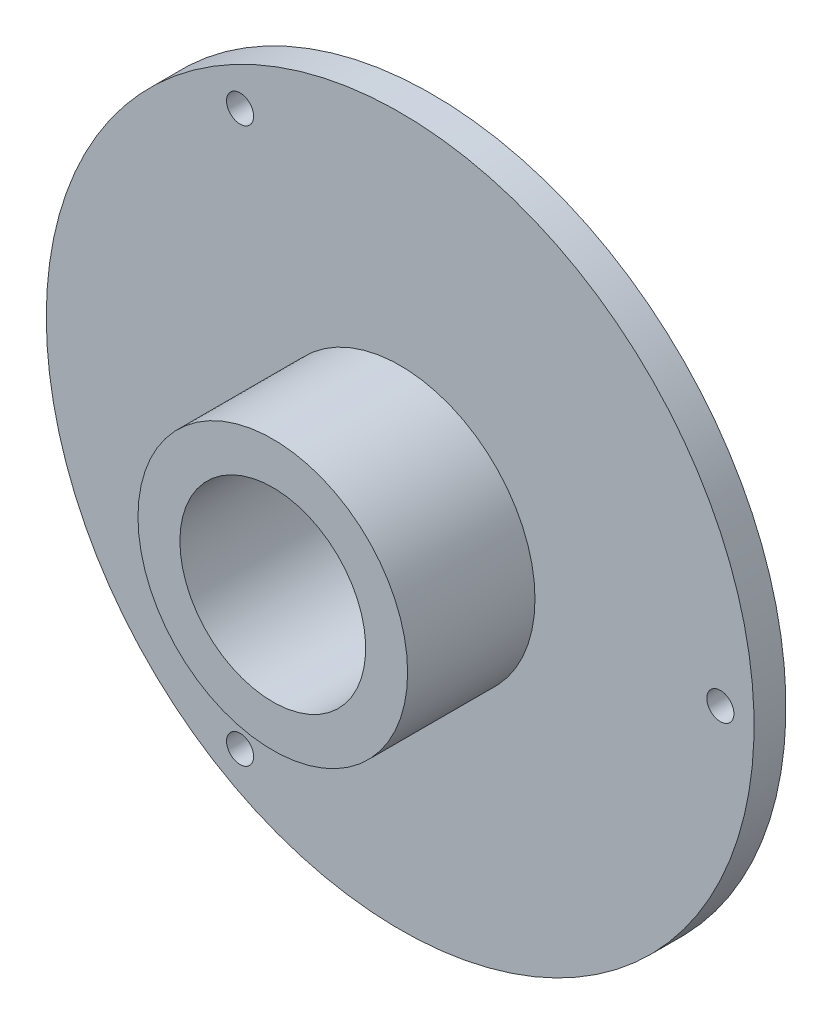
SolidWorks part; units mm, degrees
material "6061-T6 (SS)"
ref_plane "Front Plane" through (0, 0, 0) normal (0, 0, 1) x (1, 0, 0)
ref_plane "Top Plane" through (0, 0, 0) normal (0, 1, 0) x (1, 0, 0)
ref_plane "Right Plane" through (0, 0, 0) normal (1, 0, 0) x (0, 0, -1)
curve "Volute Curve"
  spline degree 3 poles (35.9487, 0, 0) (35.9516, 0.0754, 0) (35.9573, 0.2262, 0) (35.9642, 0.4524, 0) (35.9698, 0.6788, 0) (35.9739, 0.9052, 0) (35.9766, 1.1318, 0) (35.9779, 1.3583, 0) (35.9778, 1.585, 0) (35.9763, 1.8117, 0) (35.9733, 2.0385, 0) (35.969, 2.2653, 0) (35.9632, 2.4921, 0) (35.956, 2.7189, 0) (35.9473, 2.9457, 0) (35.9373, 3.1726, 0) (35.9258, 3.3994, 0) (35.9129, 3.6262, 0) (35.8986, 3.853, 0) (35.8828, 4.0798, 0) (35.8656, 4.3065, 0) (35.847, 4.5331, 0) (35.827, 4.7597, 0) (35.8055, 4.9862, 0) (35.7826, 5.2127, 0) (35.7583, 5.439, 0) (35.7326, 5.6653, 0) (35.7054, 5.8914, 0) (35.6768, 6.1174, 0) (35.6468, 6.3433, 0) (35.6153, 6.5691, 0) (35.5825, 6.7947, 0) (35.5482, 7.0201, 0) (35.5124, 7.2455, 0) (35.4753, 7.4706, 0) (35.4367, 7.6955, 0) (35.3967, 7.9203, 0) (35.3553, 8.1449, 0) (35.3125, 8.3692, 0) (35.2683, 8.5934, 0) (35.2226, 8.8173, 0) (35.1755, 9.041, 0) (35.127, 9.2644, 0) (35.0771, 9.4876, 0) (35.0257, 9.7105, 0) (34.973, 9.9332, 0) (34.9188, 10.1556, 0) (34.8633, 10.3777, 0) (34.8063, 10.5995, 0) (34.7479, 10.821, 0) (34.6881, 11.0422, 0) (34.6269, 11.263, 0) (34.5643, 11.4836, 0) (34.5004, 11.7037, 0) (34.435, 11.9236, 0) (34.3682, 12.1431, 0) (34.3, 12.3622, 0) (34.2304, 12.5809, 0) (34.1594, 12.7993, 0) (34.0871, 13.0172, 0) (34.0133, 13.2348, 0) (33.9382, 13.4519, 0) (33.8617, 13.6686, 0) (33.7838, 13.8849, 0) (33.7045, 14.1008, 0) (33.6238, 14.3162, 0) (33.5418, 14.5311, 0) (33.4584, 14.7456, 0) (33.3737, 14.9596, 0) (33.2875, 15.1732, 0) (33.2, 15.3862, 0) (33.1112, 15.5988, 0) (33.021, 15.8108, 0) (32.9294, 16.0223, 0) (32.8365, 16.2333, 0) (32.7422, 16.4438, 0) (32.6466, 16.6537, 0) (32.5497, 16.8631, 0) (32.4514, 17.0719, 0) (32.3517, 17.2801, 0) (32.2508, 17.4878, 0) (32.1485, 17.6949, 0) (32.0448, 17.9013, 0) (31.9399, 18.1072, 0) (31.8336, 18.3125, 0) (31.7261, 18.5171, 0) (31.6172, 18.7212, 0) (31.507, 18.9246, 0) (31.3955, 19.1273, 0) (31.2827, 19.3294, 0) (31.1685, 19.5308, 0) (31.0531, 19.7316, 0) (30.9365, 19.9317, 0) (30.8185, 20.1311, 0) (30.6992, 20.3298, 0) (30.5787, 20.5278, 0) (30.4569, 20.7251, 0) (30.3338, 20.9217, 0) (30.2094, 21.1175, 0) (30.0838, 21.3126, 0) (29.957, 21.507, 0) (29.8288, 21.7006, 0) (29.6995, 21.8935, 0) (29.5689, 22.0856, 0) (29.437, 22.2769, 0) (29.3039, 22.4674, 0) (29.1696, 22.6571, 0) (29.0341, 22.8461, 0) (28.8973, 23.0342, 0) (28.7593, 23.2215, 0) (28.6201, 23.408, 0) (28.4797, 23.5937, 0) (28.3381, 23.7785, 0) (28.1953, 23.9625, 0) (28.0514, 24.1456, 0) (27.9062, 24.3279, 0) (27.7598, 24.5093, 0) (27.6123, 24.6898, 0) (27.4636, 24.8694, 0) (27.3137, 25.0482, 0) (27.1627, 25.226, 0) (27.0105, 25.403, 0) (26.8572, 25.579, 0) (26.7027, 25.7541, 0) (26.5471, 25.9282, 0) (26.3903, 26.1015, 0) (26.2325, 26.2738, 0) (26.0735, 26.4451, 0) (25.9134, 26.6155, 0) (25.7521, 26.7849, 0) (25.5898, 26.9533, 0) (25.4264, 27.1208, 0) (25.2619, 27.2872, 0) (25.0963, 27.4527, 0) (24.9296, 27.6172, 0) (24.7618, 27.7806, 0) (24.593, 27.9431, 0) (24.4231, 28.1045, 0) (24.2521, 28.2649, 0) (24.0802, 28.4242, 0) (23.9071, 28.5825, 0) (23.733, 28.7398, 0) (23.5579, 28.896, 0) (23.3818, 29.0511, 0) (23.2046, 29.2052, 0) (23.0265, 29.3582, 0) (22.8473, 29.5101, 0) (22.6671, 29.6609, 0) (22.486, 29.8106, 0) (22.3038, 29.9592, 0) (22.1207, 30.1067, 0) (21.9366, 30.2531, 0) (21.7515, 30.3984, 0) (21.5655, 30.5425, 0) (21.3785, 30.6855, 0) (21.1906, 30.8274, 0) (21.0018, 30.9681, 0) (20.812, 31.1076, 0) (20.6213, 31.246, 0) (20.4297, 31.3833, 0) (20.2371, 31.5193, 0) (20.0437, 31.6542, 0) (19.8494, 31.7879, 0) (19.6541, 31.9204, 0) (19.458, 32.0517, 0) (19.2611, 32.1818, 0) (19.0632, 32.3106, 0) (18.8645, 32.4383, 0) (18.665, 32.5648, 0) (18.4646, 32.69, 0) (18.2634, 32.814, 0) (18.0613, 32.9368, 0) (17.8584, 33.0583, 0) (17.6547, 33.1786, 0) (17.4502, 33.2976, 0) (17.2449, 33.4154, 0) (17.0389, 33.5319, 0) (16.832, 33.6471, 0) (16.6244, 33.761, 0) (16.4159, 33.8737, 0) (16.2068, 33.9851, 0) (15.9969, 34.0952, 0) (15.7862, 34.204, 0) (15.5748, 34.3115, 0) (15.3627, 34.4177, 0) (15.1498, 34.5226, 0) (14.9363, 34.6262, 0) (14.722, 34.7285, 0) (14.5071, 34.8294, 0) (14.2914, 34.929, 0) (14.0751, 35.0273, 0) (13.8581, 35.1242, 0) (13.6405, 35.2198, 0) (13.4222, 35.3141, 0) (13.2032, 35.407, 0) (12.9836, 35.4985, 0) (12.7634, 35.5887, 0) (12.5426, 35.6775, 0) (12.3212, 35.765, 0) (12.0991, 35.8511, 0) (11.8765, 35.9358, 0) (11.6532, 36.0191, 0) (11.4294, 36.101, 0) (11.205, 36.1816, 0) (10.9801, 36.2607, 0) (10.7546, 36.3385, 0) (10.5286, 36.4148, 0) (10.302, 36.4898, 0) (10.0749, 36.5633, 0) (9.8473, 36.6355, 0) (9.6192, 36.7062, 0) (9.3906, 36.7755, 0) (9.1615, 36.8434, 0) (8.9319, 36.9098, 0) (8.7018, 36.9748, 0) (8.4713, 37.0384, 0) (8.2403, 37.1006, 0) (8.0089, 37.1613, 0) (7.777, 37.2206, 0) (7.5447, 37.2784, 0) (7.312, 37.3348, 0) (7.0789, 37.3897, 0) (6.8453, 37.4432, 0) (6.6114, 37.4952, 0) (6.3771, 37.5458, 0) (6.1424, 37.5949, 0) (5.9074, 37.6425, 0) (5.672, 37.6887, 0) (5.4362, 37.7334, 0) (5.2002, 37.7766, 0) (4.9637, 37.8183, 0) (4.727, 37.8586, 0) (4.49, 37.8974, 0) (4.2526, 37.9347, 0) (4.015, 37.9705, 0) (3.7771, 38.0048, 0) (3.5389, 38.0377, 0) (3.3004, 38.069, 0) (3.0617, 38.0989, 0) (2.8228, 38.1273, 0) (2.5836, 38.1541, 0) (2.3442, 38.1795, 0) (2.1046, 38.2034, 0) (1.8647, 38.2257, 0) (1.6247, 38.2466, 0) (1.3845, 38.2659, 0) (1.1441, 38.2838, 0) (0.9035, 38.3001, 0) (0.6628, 38.315, 0) (0.4219, 38.3283, 0) (0.1808, 38.3401, 0) (-0.0603, 38.3504, 0) (-0.3016, 38.3591, 0) (-0.543, 38.3664, 0) (-0.7845, 38.3721, 0) (-1.0261, 38.3764, 0) (-1.2677, 38.3791, 0) (-1.5095, 38.3802, 0) (-1.7513, 38.3799, 0) (-1.9932, 38.378, 0) (-2.2351, 38.3746, 0) (-2.477, 38.3697, 0) (-2.719, 38.3633, 0) (-2.961, 38.3554, 0) (-3.203, 38.3459, 0) (-3.445, 38.3349, 0) (-3.687, 38.3223, 0) (-3.929, 38.3083, 0) (-4.1709, 38.2927, 0) (-4.4128, 38.2756, 0) (-4.6546, 38.2569, 0) (-4.8964, 38.2368, 0) (-5.1381, 38.2151, 0) (-5.3798, 38.1919, 0) (-5.6213, 38.1671, 0) (-5.8628, 38.1408, 0) (-6.1041, 38.113, 0) (-6.3453, 38.0837, 0) (-6.5864, 38.0529, 0) (-6.8274, 38.0205, 0) (-7.0682, 37.9866, 0) (-7.3089, 37.9512, 0) (-7.5494, 37.9142, 0) (-7.7897, 37.8758, 0) (-8.0298, 37.8358, 0) (-8.2698, 37.7943, 0) (-8.5095, 37.7512, 0) (-8.749, 37.7067, 0) (-8.9883, 37.6606, 0) (-9.2274, 37.613, 0) (-9.4662, 37.5639, 0) (-9.7048, 37.5133, 0) (-9.9431, 37.4612, 0) (-10.1811, 37.4076, 0) (-10.4189, 37.3524, 0) (-10.6563, 37.2957, 0) (-10.8935, 37.2376, 0) (-11.1303, 37.1779, 0) (-11.3669, 37.1167, 0) (-11.6031, 37.054, 0) (-11.8389, 36.9898, 0) (-12.0745, 36.9241, 0) (-12.3096, 36.857, 0) (-12.5444, 36.7883, 0) (-12.7788, 36.7181, 0) (-13.0129, 36.6464, 0) (-13.2465, 36.5733, 0) (-13.4797, 36.4986, 0) (-13.7126, 36.4225, 0) (-13.9449, 36.3449, 0) (-14.1769, 36.2658, 0) (-14.4084, 36.1852, 0) (-14.6395, 36.1032, 0) (-14.8701, 36.0196, 0) (-15.1002, 35.9346, 0) (-15.3299, 35.8482, 0) (-15.559, 35.7602, 0) (-15.7877, 35.6708, 0) (-16.0159, 35.58, 0) (-16.2435, 35.4877, 0) (-16.4706, 35.3939, 0) (-16.6972, 35.2987, 0) (-16.9232, 35.202, 0) (-17.1487, 35.1039, 0) (-17.3736, 35.0043, 0) (-17.5979, 34.9033, 0) (-17.8217, 34.8009, 0) (-18.0448, 34.697, 0) (-18.2674, 34.5917, 0) (-18.4893, 34.485, 0) (-18.7107, 34.3769, 0) (-18.9314, 34.2673, 0) (-19.1514, 34.1563, 0) (-19.3708, 34.044, 0) (-19.5896, 33.9302, 0) (-19.8077, 33.815, 0) (-20.0251, 33.6984, 0) (-20.2419, 33.5804, 0) (-20.4579, 33.461, 0) (-20.6733, 33.3402, 0) (-20.8879, 33.218, 0) (-21.1018, 33.0945, 0) (-21.315, 32.9696, 0) (-21.5275, 32.8433, 0) (-21.7392, 32.7156, 0) (-21.9501, 32.5866, 0) (-22.1603, 32.4562, 0) (-22.3698, 32.3245, 0) (-22.5784, 32.1914, 0) (-22.7863, 32.057, 0) (-22.9933, 31.9212, 0) (-23.1996, 31.7841, 0) (-23.405, 31.6457, 0) (-23.6097, 31.5059, 0) (-23.8134, 31.3648, 0) (-24.0164, 31.2224, 0) (-24.2185, 31.0787, 0) (-24.4197, 30.9337, 0) (-24.6201, 30.7874, 0) (-24.8196, 30.6398, 0) (-25.0182, 30.4909, 0) (-25.216, 30.3407, 0) (-25.4128, 30.1892, 0) (-25.6087, 30.0365, 0) (-25.8037, 29.8825, 0) (-25.9978, 29.7272, 0) (-26.191, 29.5707, 0) (-26.3832, 29.4129, 0) (-26.5745, 29.2539, 0) (-26.7648, 29.0936, 0) (-26.9541, 28.9321, 0) (-27.1425, 28.7693, 0) (-27.3299, 28.6054, 0) (-27.5163, 28.4402, 0) (-27.7017, 28.2738, 0) (-27.8861, 28.1062, 0) (-28.0695, 27.9374, 0) (-28.2519, 27.7674, 0) (-28.4332, 27.5962, 0) (-28.6135, 27.4238, 0) (-28.7928, 27.2503, 0) (-28.971, 27.0756, 0) (-29.1482, 26.8997, 0) (-29.3243, 26.7227, 0) (-29.4993, 26.5445, 0) (-29.6733, 26.3652, 0) (-29.8461, 26.1847, 0) (-30.0179, 26.0031, 0) (-30.1885, 25.8204, 0) (-30.3581, 25.6366, 0) (-30.5265, 25.4516, 0) (-30.6938, 25.2656, 0) (-30.86, 25.0784, 0) (-31.025, 24.8902, 0) (-31.1889, 24.7009, 0) (-31.3516, 24.5105, 0) (-31.5132, 24.319, 0) (-31.6736, 24.1265, 0) (-31.8329, 23.9329, 0) (-31.9909, 23.7382, 0) (-32.1478, 23.5426, 0) (-32.3034, 23.3459, 0) (-32.4579, 23.1481, 0) (-32.6112, 22.9494, 0) (-32.7632, 22.7496, 0) (-32.914, 22.5489, 0) (-33.0636, 22.3471, 0) (-33.212, 22.1443, 0) (-33.3591, 21.9406, 0) (-33.505, 21.7359, 0) (-33.6496, 21.5302, 0) (-33.7929, 21.3236, 0) (-33.935, 21.116, 0) (-34.0758, 20.9075, 0) (-34.2154, 20.698, 0) (-34.3536, 20.4876, 0) (-34.4906, 20.2763, 0) (-34.6262, 20.0641, 0) (-34.7606, 19.851, 0) (-34.8936, 19.637, 0) (-35.0253, 19.4221, 0) (-35.1557, 19.2063, 0) (-35.2848, 18.9896, 0) (-35.4126, 18.7721, 0) (-35.539, 18.5537, 0) (-35.664, 18.3345, 0) (-35.7877, 18.1144, 0) (-35.9101, 17.8935, 0) (-36.0311, 17.6718, 0) (-36.1507, 17.4493, 0) (-36.2689, 17.2259, 0) (-36.3858, 17.0018, 0) (-36.5013, 16.7769, 0) (-36.6154, 16.5512, 0) (-36.7281, 16.3247, 0) (-36.8394, 16.0975, 0) (-36.9493, 15.8695, 0) (-37.0578, 15.6408, 0) (-37.1649, 15.4113, 0) (-37.2705, 15.1811, 0) (-37.3748, 14.9502, 0) (-37.4776, 14.7186, 0) (-37.5789, 14.4862, 0) (-37.6789, 14.2532, 0) (-37.7773, 14.0195, 0) (-37.8744, 13.7851, 0) (-37.97, 13.5501, 0) (-38.0641, 13.3144, 0) (-38.1567, 13.078, 0) (-38.2479, 12.8411, 0) (-38.3377, 12.6034, 0) (-38.4259, 12.3652, 0) (-38.5127, 12.1264, 0) (-38.598, 11.8869, 0) (-38.6818, 11.6469, 0) (-38.7641, 11.4062, 0) (-38.8449, 11.165, 0) (-38.9242, 10.9233, 0) (-39.002, 10.6809, 0) (-39.0783, 10.4381, 0) (-39.1531, 10.1947, 0) (-39.2264, 9.9507, 0) (-39.2982, 9.7063, 0) (-39.3684, 9.4613, 0) (-39.4371, 9.2159, 0) (-39.5043, 8.9699, 0) (-39.57, 8.7235, 0) (-39.6341, 8.4766, 0) (-39.6966, 8.2292, 0) (-39.7577, 7.9814, 0) (-39.8172, 7.7332, 0) (-39.8751, 7.4845, 0) (-39.9315, 7.2354, 0) (-39.9863, 6.9858, 0) (-40.0396, 6.7359, 0) (-40.0913, 6.4856, 0) (-40.1414, 6.2349, 0) (-40.19, 5.9838, 0) (-40.237, 5.7324, 0) (-40.2825, 5.4806, 0) (-40.3263, 5.2284, 0) (-40.3686, 4.976, 0) (-40.4093, 4.7232, 0) (-40.4484, 4.47, 0) (-40.486, 4.2166, 0) (-40.5219, 3.9629, 0) (-40.5563, 3.7089, 0) (-40.5891, 3.4546, 0) (-40.6203, 3.2001, 0) (-40.6498, 2.9453, 0) (-40.6778, 2.6902, 0) (-40.7042, 2.435, 0) (-40.729, 2.1795, 0) (-40.7522, 1.9237, 0) (-40.7738, 1.6678, 0) (-40.7937, 1.4117, 0) (-40.8121, 1.1554, 0) (-40.8289, 0.8989, 0) (-40.844, 0.6423, 0) (-40.8575, 0.3855, 0) (-40.8695, 0.1285, 0) (-40.8798, -0.1286, 0) (-40.8884, -0.3858, 0) (-40.8955, -0.6431, 0) (-40.901, -0.9005, 0) (-40.9048, -1.158, 0) (-40.907, -1.4156, 0) (-40.9076, -1.6733, 0) (-40.9066, -1.931, 0) (-40.9039, -2.1888, 0) (-40.8996, -2.4467, 0) (-40.8937, -2.7045, 0) (-40.8862, -2.9624, 0) (-40.8771, -3.2203, 0) (-40.8663, -3.4782, 0) (-40.8539, -3.7361, 0) (-40.8399, -3.994, 0) (-40.8242, -4.2519, 0) (-40.8069, -4.5097, 0) (-40.788, -4.7674, 0) (-40.7675, -5.0251, 0) (-40.7453, -5.2828, 0) (-40.7215, -5.5403, 0) (-40.6961, -5.7978, 0) (-40.669, -6.0552, 0) (-40.6404, -6.3124, 0) (-40.6101, -6.5695, 0) (-40.5781, -6.8265, 0) (-40.5446, -7.0834, 0) (-40.5094, -7.3401, 0) (-40.4726, -7.5967, 0) (-40.4342, -7.853, 0) (-40.3941, -8.1092, 0) (-40.3525, -8.3652, 0) (-40.3092, -8.621, 0) (-40.2643, -8.8766, 0) (-40.2177, -9.1319, 0) (-40.1696, -9.3871, 0) (-40.1198, -9.6419, 0) (-40.0684, -9.8966, 0) (-40.0154, -10.1509, 0) (-39.9608, -10.405, 0) (-39.9046, -10.6588, 0) (-39.8468, -10.9123, 0) (-39.7873, -11.1655, 0) (-39.7263, -11.4184, 0) (-39.6636, -11.6709, 0) (-39.5994, -11.9232, 0) (-39.5335, -12.175, 0) (-39.466, -12.4265, 0) (-39.397, -12.6777, 0) (-39.3263, -12.9285, 0) (-39.254, -13.1789, 0) (-39.1802, -13.4288, 0) (-39.1048, -13.6784, 0) (-39.0277, -13.9276, 0) (-38.9491, -14.1763, 0) (-38.8689, -14.4246, 0) (-38.7871, -14.6725, 0) (-38.7038, -14.9199, 0) (-38.6188, -15.1668, 0) (-38.5323, -15.4132, 0) (-38.4442, -15.6592, 0) (-38.3546, -15.9047, 0) (-38.2634, -16.1496, 0) (-38.1706, -16.3941, 0) (-38.0762, -16.638, 0) (-37.9803, -16.8813, 0) (-37.8829, -17.1242, 0) (-37.7839, -17.3664, 0) (-37.6833, -17.6081, 0) (-37.5812, -17.8492, 0) (-37.4776, -18.0898, 0) (-37.3724, -18.3297, 0) (-37.2657, -18.569, 0) (-37.1574, -18.8077, 0) (-37.0477, -19.0458, 0) (-36.9364, -19.2833, 0) (-36.8236, -19.5201, 0) (-36.7092, -19.7562, 0) (-36.5934, -19.9917, 0) (-36.476, -20.2265, 0) (-36.3572, -20.4606, 0) (-36.2368, -20.694, 0) (-36.1149, -20.9268, 0) (-35.9916, -21.1588, 0) (-35.8667, -21.3901, 0) (-35.7404, -21.6206, 0) (-35.6126, -21.8504, 0) (-35.4833, -22.0795, 0) (-35.3526, -22.3078, 0) (-35.2203, -22.5353, 0) (-35.0867, -22.762, 0) (-34.9515, -22.988, 0) (-34.8149, -23.2131, 0) (-34.6769, -23.4375, 0) (-34.5374, -23.661, 0) (-34.3964, -23.8837, 0) (-34.2541, -24.1056, 0) (-34.1103, -24.3266, 0) (-33.9651, -24.5468, 0) (-33.8184, -24.7661, 0) (-33.6704, -24.9845, 0) (-33.5209, -25.202, 0) (-33.3701, -25.4187, 0) (-33.2178, -25.6345, 0) (-33.0641, -25.8493, 0) (-32.9091, -26.0632, 0) (-32.7527, -26.2762, 0) (-32.5949, -26.4883, 0) (-32.4357, -26.6994, 0) (-32.2751, -26.9096, 0) (-32.1132, -27.1188, 0) (-31.95, -27.327, 0) (-31.7854, -27.5343, 0) (-31.6194, -27.7405, 0) (-31.4522, -27.9458, 0) (-31.2835, -28.15, 0) (-31.1136, -28.3533, 0) (-30.9424, -28.5555, 0) (-30.7698, -28.7567, 0) (-30.5959, -28.9568, 0) (-30.4207, -29.1559, 0) (-30.2443, -29.354, 0) (-30.0665, -29.5509, 0) (-29.8875, -29.7468, 0) (-29.7072, -29.9417, 0) (-29.5256, -30.1354, 0) (-29.3428, -30.328, 0) (-29.1587, -30.5195, 0) (-28.9733, -30.7099, 0) (-28.7867, -30.8992, 0) (-28.5989, -31.0874, 0) (-28.4099, -31.2744, 0) (-28.2196, -31.4602, 0) (-28.0281, -31.6449, 0) (-27.8354, -31.8285, 0) (-27.6416, -32.0109, 0) (-27.4465, -32.1921, 0) (-27.2502, -32.3721, 0) (-27.0528, -32.5509, 0) (-26.8542, -32.7285, 0) (-26.6544, -32.9049, 0) (-26.4535, -33.0801, 0) (-26.2514, -33.254, 0) (-26.0482, -33.4267, 0) (-25.8438, -33.5982, 0) (-25.6383, -33.7685, 0) (-25.4317, -33.9374, 0) (-25.224, -34.1052, 0) (-25.0152, -34.2716, 0) (-24.8053, -34.4368, 0) (-24.5943, -34.6007, 0) (-24.3822, -34.7633, 0) (-24.1691, -34.9246, 0) (-23.9549, -35.0846, 0) (-23.7396, -35.2432, 0) (-23.5233, -35.4006, 0) (-23.3059, -35.5566, 0) (-23.0876, -35.7113, 0) (-22.8681, -35.8647, 0) (-22.6477, -36.0167, 0) (-22.4263, -36.1674, 0) (-22.2039, -36.3167, 0) (-21.9804, -36.4646, 0) (-21.756, -36.6112, 0) (-21.5306, -36.7564, 0) (-21.3043, -36.9002, 0) (-21.077, -37.0426, 0) (-20.8488, -37.1836, 0) (-20.6196, -37.3232, 0) (-20.3894, -37.4614, 0) (-20.1584, -37.5981, 0) (-19.9264, -37.7335, 0) (-19.6936, -37.8674, 0) (-19.4598, -37.9999, 0) (-19.2252, -38.1309, 0) (-18.9897, -38.2605, 0) (-18.7533, -38.3886, 0) (-18.516, -38.5153, 0) (-18.2779, -38.6405, 0) (-18.039, -38.7643, 0) (-17.7992, -38.8866, 0) (-17.5586, -39.0073, 0) (-17.3172, -39.1266, 0) (-17.075, -39.2444, 0) (-16.8319, -39.3607, 0) (-16.5881, -39.4755, 0) (-16.3436, -39.5888, 0) (-16.0982, -39.7006, 0) (-15.8521, -39.8109, 0) (-15.6052, -39.9196, 0) (-15.3576, -40.0268, 0) (-15.1093, -40.1325, 0) (-14.8602, -40.2366, 0) (-14.6105, -40.3392, 0) (-14.36, -40.4402, 0) (-14.1088, -40.5397, 0) (-13.857, -40.6377, 0) (-13.6045, -40.734, 0) (-13.3513, -40.8288, 0) (-13.0975, -40.922, 0) (-12.843, -41.0137, 0) (-12.5879, -41.1037, 0) (-12.3321, -41.1922, 0) (-12.0758, -41.2791, 0) (-11.8188, -41.3644, 0) (-11.5613, -41.4481, 0) (-11.3031, -41.5302, 0) (-11.0444, -41.6106, 0) (-10.7851, -41.6895, 0) (-10.5253, -41.7668, 0) (-10.2649, -41.8424, 0) (-10.004, -41.9164, 0) (-9.7426, -41.9888, 0) (-9.4806, -42.0596, 0) (-9.2182, -42.1287, 0) (-8.9552, -42.1962, 0) (-8.6918, -42.262, 0) (-8.4279, -42.3262, 0) (-8.1635, -42.3888, 0) (-7.8987, -42.4497, 0) (-7.6334, -42.509, 0) (-7.3677, -42.5666, 0) (-7.1016, -42.6225, 0) (-6.835, -42.6768, 0) (-6.5681, -42.7294, 0) (-6.3007, -42.7803, 0) (-6.033, -42.8296, 0) (-5.7649, -42.8772, 0) (-5.4965, -42.9231, 0) (-5.2277, -42.9673, 0) (-4.9586, -43.0099, 0) (-4.6891, -43.0508, 0) (-4.4194, -43.0899, 0) (-4.1493, -43.1274, 0) (-3.8789, -43.1632, 0) (-3.6082, -43.1973, 0) (-3.3373, -43.2298, 0) (-3.0661, -43.2605, 0) (-2.7946, -43.2895, 0) (-2.5229, -43.3168, 0) (-2.251, -43.3424, 0) (-1.9788, -43.3663, 0) (-1.7064, -43.3885, 0) (-1.4339, -43.4089, 0) (-1.1611, -43.4277, 0) (-0.8882, -43.4448, 0) (-0.615, -43.4601, 0) (-0.3418, -43.4737, 0) (-0.0684, -43.4856, 0) (0.2052, -43.4958, 0) (0.4789, -43.5043, 0) (0.7527, -43.511, 0) (1.0266, -43.516, 0) (1.3005, -43.5193, 0) (1.5746, -43.5209, 0) (1.8488, -43.5208, 0) (2.123, -43.5189, 0) (2.3972, -43.5153, 0) (2.6715, -43.5099, 0) (2.9458, -43.5029, 0) (3.2201, -43.4941, 0) (3.4945, -43.4836, 0) (3.7688, -43.4713, 0) (4.0431, -43.4574, 0) (4.3174, -43.4417, 0) (4.5917, -43.4242, 0) (4.8659, -43.405, 0) (5.1401, -43.3841, 0) (5.4141, -43.3615, 0) (5.6881, -43.3372, 0) (5.962, -43.3111, 0) (6.2358, -43.2832, 0) (6.5095, -43.2537, 0) (6.7831, -43.2224, 0) (7.0565, -43.1894, 0) (7.3298, -43.1547, 0) (7.6029, -43.1182, 0) (7.8759, -43.08, 0) (8.1486, -43.0401, 0) (8.4212, -42.9984, 0) (8.6936, -42.955, 0) (8.9658, -42.9099, 0) (9.2377, -42.8631, 0) (9.5094, -42.8146, 0) (9.7809, -42.7643, 0) (10.0521, -42.7123, 0) (10.3231, -42.6586, 0) (10.5937, -42.6032, 0) (10.8641, -42.546, 0) (11.1342, -42.4872, 0) (11.4039, -42.4266, 0) (11.6734, -42.3643, 0) (11.9425, -42.3003, 0) (12.2113, -42.2346, 0) (12.4797, -42.1672, 0) (12.7477, -42.0981, 0) (13.0154, -42.0273, 0) (13.2827, -41.9548, 0) (13.5496, -41.8805, 0) (13.8161, -41.8046, 0) (14.0822, -41.727, 0) (14.3478, -41.6477, 0) (14.613, -41.5667, 0) (14.8777, -41.4841, 0) (15.142, -41.3997, 0) (15.4058, -41.3136, 0) (15.6692, -41.2259, 0) (15.932, -41.1365, 0) (16.1943, -41.0454, 0) (16.4562, -40.9527, 0) (16.7174, -40.8583, 0) (16.9782, -40.7622, 0) (17.2384, -40.6644, 0) (17.498, -40.565, 0) (17.7571, -40.4639, 0) (18.0156, -40.3612, 0) (18.2735, -40.2568, 0) (18.5309, -40.1508, 0) (18.7876, -40.0432, 0) (19.0436, -39.9339, 0) (19.2991, -39.8229, 0) (19.5539, -39.7104, 0) (19.808, -39.5962, 0) (20.0615, -39.4803, 0) (20.3144, -39.3629, 0) (20.5665, -39.2438, 0) (20.8179, -39.1231, 0) (21.0687, -39.0008, 0) (21.3187, -38.877, 0) (21.568, -38.7515, 0) (21.8166, -38.6244, 0) (22.0644, -38.4957, 0) (22.3114, -38.3654, 0) (22.5577, -38.2335, 0) (22.8033, -38.1001, 0) (23.048, -37.9651, 0) (23.2919, -37.8285, 0) (23.5351, -37.6903, 0) (23.7774, -37.5506, 0) (24.0189, -37.4094, 0) (24.2595, -37.2665, 0) (24.4993, -37.1222, 0) (24.7383, -36.9762, 0) (24.9764, -36.8288, 0) (25.2136, -36.6798, 0) (25.4499, -36.5293, 0) (25.6854, -36.3773, 0) (25.9199, -36.2237, 0) (26.1535, -36.0687, 0) (26.3862, -35.9121, 0) (26.6179, -35.7541, 0) (26.8487, -35.5945, 0) (27.0786, -35.4335, 0) (27.3075, -35.271, 0) (27.5354, -35.1069, 0) (27.7623, -34.9415, 0) (27.9883, -34.7745, 0) (28.2132, -34.6061, 0) (28.4372, -34.4363, 0) (28.6601, -34.265, 0) (28.882, -34.0923, 0) (29.1028, -33.9181, 0) (29.3226, -33.7425, 0) (29.5413, -33.5655, 0) (29.759, -33.387, 0) (29.9756, -33.2072, 0) (30.1911, -33.0259, 0) (30.4055, -32.8433, 0) (30.6188, -32.6592, 0) (30.831, -32.4738, 0) (31.0421, -32.287, 0) (31.2521, -32.0988, 0) (31.4609, -31.9093, 0) (31.6686, -31.7184, 0) (31.8751, -31.5261, 0) (32.0804, -31.3326, 0) (32.2846, -31.1376, 0) (32.4876, -30.9414, 0) (32.6894, -30.7438, 0) (32.89, -30.5449, 0) (33.0894, -30.3447, 0) (33.2875, -30.1433, 0) (33.4845, -29.9405, 0) (33.6802, -29.7364, 0) (33.8747, -29.5311, 0) (34.0679, -29.3244, 0) (34.2599, -29.1166, 0) (34.4506, -28.9074, 0) (34.64, -28.6971, 0) (34.8281, -28.4855, 0) (35.015, -28.2726, 0) (35.2005, -28.0585, 0) (35.3848, -27.8433, 0) (35.5677, -27.6268, 0) (35.7493, -27.4091, 0) (35.9296, -27.1902, 0) (36.1085, -26.9701, 0) (36.2861, -26.7489, 0) (36.4623, -26.5265, 0) (36.6372, -26.3029, 0) (36.8107, -26.0782, 0) (36.9828, -25.8523, 0) (37.1536, -25.6254, 0) (37.3229, -25.3972, 0) (37.4909, -25.168, 0) (37.6574, -24.9377, 0) (37.8226, -24.7062, 0) (37.9863, -24.4737, 0) (38.1486, -24.2401, 0) (38.3094, -24.0054, 0) (38.4688, -23.7697, 0) (38.6268, -23.5329, 0) (38.7833, -23.295, 0) (38.9383, -23.0561, 0) (39.0919, -22.8162, 0) (39.2439, -22.5753, 0) (39.3945, -22.3333, 0) (39.5437, -22.0904, 0) (39.6913, -21.8465, 0) (39.8374, -21.6015, 0) (39.982, -21.3557, 0) (40.1251, -21.1088, 0) (40.2666, -20.861, 0) (40.4067, -20.6122, 0) (40.5452, -20.3625, 0) (40.6821, -20.1119, 0) (40.8175, -19.8604, 0) (40.9514, -19.6079, 0) (41.0837, -19.3546, 0) (41.2144, -19.1004, 0) (41.3436, -18.8453, 0) (41.4711, -18.5893, 0) (41.5971, -18.3325, 0) (41.7215, -18.0748, 0) (41.8444, -17.8162, 0) (41.9656, -17.5569, 0) (42.0852, -17.2967, 0) (42.2031, -17.0357, 0) (42.3195, -16.7739, 0) (42.4343, -16.5114, 0) (42.5474, -16.248, 0) (42.6589, -15.9839, 0) (42.7687, -15.719, 0) (42.8769, -15.4534, 0) (42.9835, -15.187, 0) (43.0884, -14.9199, 0) (43.1916, -14.6521, 0) (43.2932, -14.3836, 0) (43.3931, -14.1144, 0) (43.4913, -13.8444, 0) (43.5879, -13.5739, 0) (43.6828, -13.3026, 0) (43.776, -13.0307, 0) (43.8675, -12.7581, 0) (43.9573, -12.4849, 0) (44.0454, -12.2111, 0) (44.1318, -11.9367, 0) (44.2164, -11.6617, 0) (44.2994, -11.386, 0) (44.3807, -11.1098, 0) (44.4602, -10.833, 0) (44.538, -10.5557, 0) (44.6141, -10.2778, 0) (44.6884, -9.9994, 0) (44.761, -9.7204, 0) (44.8319, -9.4409, 0) (44.901, -9.1609, 0) (44.9684, -8.8805, 0) (45.034, -8.5995, 0) (45.0979, -8.3181, 0) (45.16, -8.0362, 0) (45.2204, -7.7538, 0) (45.279, -7.471, 0) (45.3358, -7.1878, 0) (45.3908, -6.9041, 0) (45.4441, -6.6201, 0) (45.4956, -6.3356, 0) (45.5453, -6.0508, 0) (45.5932, -5.7656, 0) (45.6394, -5.48, 0) (45.6837, -5.1941, 0) (45.7263, -4.9078, 0) (45.7671, -4.6212, 0) (45.8061, -4.3343, 0) (45.8432, -4.0471, 0) (45.8786, -3.7596, 0) (45.9122, -3.4717, 0) (45.944, -3.1837, 0) (45.9739, -2.8953, 0) (46.0021, -2.6067, 0) (46.0284, -2.3179, 0) (46.053, -2.0288, 0) (46.0757, -1.7396, 0) (46.0966, -1.4501, 0) (46.1157, -1.1604, 0) (46.133, -0.8705, 0) (46.1484, -0.5805, 0) (46.1621, -0.2903, 0) (46.1697, -0.0968, 0) (46.1735, 0, 0) knots 0 0 0 0 0.000879 0.001759 0.002638 0.003518 0.004398 0.005279 0.006159 0.00704 0.007921 0.008802 0.009684 0.010565 0.011447 0.012329 0.013212 0.014094 0.014977 0.01586 0.016744 0.017627 0.018511 0.019395 0.020279 0.021163 0.022048 0.022933 0.023818 0.024703 0.025589 0.026475 0.027361 0.028247 0.029133 0.03002 0.030907 0.031794 0.032681 0.033569 0.034457 0.035345 0.036233 0.037122 0.03801 0.038899 0.039789 0.040678 0.041568 0.042458 0.043348 0.044238 0.045129 0.04602 0.046911 0.047802 0.048693 0.049585 0.050477 0.051369 0.052262 0.053154 0.054047 0.05494 0.055834 0.056727 0.057621 0.058515 0.05941 0.060304 0.061199 0.062094 0.062989 0.063884 0.06478 0.065676 0.066572 0.067469 0.068365 0.069262 0.070159 0.071056 0.071954 0.072852 0.07375 0.074648 0.075546 0.076445 0.077344 0.078243 0.079143 0.080042 0.080942 0.081842 0.082743 0.083643 0.084544 0.085445 0.086346 0.087248 0.08815 0.089052 0.089954 0.090856 0.091759 0.092662 0.093565 0.094468 0.095372 0.096276 0.09718 0.098084 0.098989 0.099894 0.100799 0.101704 0.102609 0.103515 0.104421 0.105327 0.106234 0.10714 0.108047 0.108954 0.109862 0.110769 0.111677 0.112585 0.113494 0.114402 0.115311 0.11622 0.117129 0.118039 0.118948 0.119858 0.120769 0.121679 0.12259 0.123501 0.124412 0.125323 0.126235 0.127147 0.128059 0.128971 0.129884 0.130797 0.13171 0.132623 0.133536 0.13445 0.135364 0.136278 0.137193 0.138108 0.139023 0.139938 0.140853 0.141769 0.142685 0.143601 0.144517 0.145434 0.146351 0.147268 0.148185 0.149103 0.15002 0.150938 0.151857 0.152775 0.153694 0.154613 0.155532 0.156452 0.157371 0.158291 0.159212 0.160132 0.161053 0.161974 0.162895 0.163816 0.164738 0.16566 0.166582 0.167504 0.168427 0.169349 0.170272 0.171196 0.172119 0.173043 0.173967 0.174891 0.175816 0.176741 0.177666 0.178591 0.179516 0.180442 0.181368 0.182294 0.18322 0.184147 0.185074 0.186001 0.186928 0.187856 0.188784 0.189712 0.19064 0.191569 0.192498 0.193427 0.194356 0.195286 0.196215 0.197145 0.198076 0.199006 0.199937 0.200868 0.201799 0.20273 0.203662 0.204594 0.205526 0.206459 0.207391 0.208324 0.209257 0.210191 0.211124 0.212058 0.212992 0.213927 0.214861 0.215796 0.216731 0.217667 0.218602 0.219538 0.220474 0.22141 0.222347 0.223284 0.224221 0.225158 0.226095 0.227033 0.227971 0.228909 0.229848 0.230787 0.231726 0.232665 0.233604 0.234544 0.235484 0.236424 0.237364 0.238305 0.239246 0.240187 0.241128 0.24207 0.243012 0.243954 0.244896 0.245839 0.246782 0.247725 0.248668 0.249612 0.250556 0.2515 0.252444 0.253389 0.254333 0.255278 0.256224 0.257169 0.258115 0.259061 0.260007 0.260954 0.2619 0.262847 0.263795 0.264742 0.26569 0.266638 0.267586 0.268534 0.269483 0.270432 0.271381 0.272331 0.27328 0.27423 0.27518 0.276131 0.277081 0.278032 0.278983 0.279935 0.280886 0.281838 0.28279 0.283743 0.284695 0.285648 0.286601 0.287555 0.288508 0.289462 0.290416 0.29137 0.292325 0.29328 0.294235 0.29519 0.296146 0.297102 0.298058 0.299014 0.29997 0.300927 0.301884 0.302841 0.303799 0.304757 0.305715 0.306673 0.307631 0.30859 0.309549 0.310508 0.311468 0.312428 0.313388 0.314348 0.315308 0.316269 0.31723 0.318191 0.319152 0.320114 0.321076 0.322038 0.323001 0.323963 0.324926 0.325889 0.326853 0.327817 0.32878 0.329745 0.330709 0.331674 0.332639 0.333604 0.334569 0.335535 0.336501 0.337467 0.338433 0.3394 0.340367 0.341334 0.342301 0.343269 0.344237 0.345205 0.346173 0.347142 0.34811 0.34908 0.350049 0.351019 0.351988 0.352958 0.353929 0.354899 0.35587 0.356841 0.357813 0.358784 0.359756 0.360728 0.3617 0.362673 0.363646 0.364619 0.365592 0.366566 0.367539 0.368514 0.369488 0.370462 0.371437 0.372412 0.373388 0.374363 0.375339 0.376315 0.377291 0.378268 0.379245 0.380222 0.381199 0.382176 0.383154 0.384132 0.38511 0.386089 0.387068 0.388047 0.389026 0.390006 0.390985 0.391965 0.392946 0.393926 0.394907 0.395888 0.396869 0.397851 0.398833 0.399815 0.400797 0.401779 0.402762 0.403745 0.404728 0.405712 0.406696 0.40768 0.408664 0.409648 0.410633 0.411618 0.412603 0.413589 0.414575 0.415561 0.416547 0.417534 0.41852 0.419507 0.420495 0.421482 0.42247 0.423458 0.424446 0.425435 0.426423 0.427412 0.428402 0.429391 0.430381 0.431371 0.432361 0.433352 0.434343 0.435334 0.436325 0.437316 0.438308 0.4393 0.440292 0.441285 0.442278 0.443271 0.444264 0.445258 0.446251 0.447245 0.44824 0.449234 0.450229 0.451224 0.452219 0.453215 0.454211 0.455207 0.456203 0.457199 0.458196 0.459193 0.460191 0.461188 0.462186 0.463184 0.464182 0.465181 0.46618 0.467179 0.468178 0.469177 0.470177 0.471177 0.472178 0.473178 0.474179 0.47518 0.476181 0.477183 0.478185 0.479187 0.480189 0.481192 0.482195 0.483198 0.484201 0.485205 0.486209 0.487213 0.488217 0.489222 0.490226 0.491232 0.492237 0.493243 0.494248 0.495255 0.496261 0.497267 0.498274 0.499281 0.500289 0.501297 0.502304 0.503313 0.504321 0.50533 0.506338 0.507348 0.508357 0.509367 0.510377 0.511387 0.512397 0.513408 0.514419 0.51543 0.516441 0.517453 0.518465 0.519477 0.52049 0.521502 0.522515 0.523528 0.524542 0.525556 0.52657 0.527584 0.528598 0.529613 0.530628 0.531643 0.532659 0.533674 0.53469 0.535707 0.536723 0.53774 0.538757 0.539774 0.540792 0.54181 0.542828 0.543846 0.544864 0.545883 0.546902 0.547921 0.548941 0.549961 0.550981 0.552001 0.553022 0.554043 0.555064 0.556085 0.557107 0.558128 0.559151 0.560173 0.561196 0.562218 0.563241 0.564265 0.565288 0.566312 0.567336 0.568361 0.569386 0.57041 0.571436 0.572461 0.573487 0.574513 0.575539 0.576565 0.577592 0.578619 0.579646 0.580673 0.581701 0.582729 0.583757 0.584786 0.585815 0.586844 0.587873 0.588902 0.589932 0.590962 0.591992 0.593023 0.594054 0.595085 0.596116 0.597147 0.598179 0.599211 0.600244 0.601276 0.602309 0.603342 0.604375 0.605409 0.606443 0.607477 0.608511 0.609546 0.610581 0.611616 0.612651 0.613687 0.614723 0.615759 0.616795 0.617832 0.618869 0.619906 0.620943 0.621981 0.623019 0.624057 0.625096 0.626134 0.627173 0.628213 0.629252 0.630292 0.631332 0.632372 0.633413 0.634453 0.635494 0.636536 0.637577 0.638619 0.639661 0.640703 0.641746 0.642789 0.643832 0.644875 0.645919 0.646963 0.648007 0.649051 0.650096 0.651141 0.652186 0.653231 0.654277 0.655323 0.656369 0.657415 0.658462 0.659509 0.660556 0.661604 0.662651 0.663699 0.664748 0.665796 0.666845 0.667894 0.668943 0.669993 0.671042 0.672092 0.673143 0.674193 0.675244 0.676295 0.677346 0.678398 0.67945 0.680502 0.681554 0.682607 0.68366 0.684713 0.685766 0.68682 0.687874 0.688928 0.689982 0.691037 0.692092 0.693147 0.694203 0.695258 0.696314 0.697371 0.698427 0.699484 0.700541 0.701598 0.702656 0.703713 0.704771 0.70583 0.706888 0.707947 0.709006 0.710066 0.711125 0.712185 0.713245 0.714305 0.715366 0.716427 0.717488 0.71855 0.719611 0.720673 0.721735 0.722798 0.72386 0.724923 0.725987 0.72705 0.728114 0.729178 0.730242 0.731307 0.732371 0.733436 0.734502 0.735567 0.736633 0.737699 0.738766 0.739832 0.740899 0.741966 0.743033 0.744101 0.745169 0.746237 0.747306 0.748374 0.749443 0.750512 0.751582 0.752652 0.753722 0.754792 0.755862 0.756933 0.758004 0.759075 0.760147 0.761219 0.762291 0.763363 0.764436 0.765508 0.766582 0.767655 0.768729 0.769802 0.770877 0.771951 0.773026 0.774101 0.775176 0.776251 0.777327 0.778403 0.779479 0.780556 0.781632 0.782709 0.783787 0.784864 0.785942 0.78702 0.788098 0.789177 0.790256 0.791335 0.792414 0.793494 0.794574 0.795654 0.796734 0.797815 0.798896 0.799977 0.801058 0.80214 0.803222 0.804304 0.805387 0.806469 0.807552 0.808636 0.809719 0.810803 0.811887 0.812971 0.814056 0.815141 0.816226 0.817311 0.818397 0.819483 0.820569 0.821655 0.822742 0.823829 0.824916 0.826004 0.827091 0.828179 0.829268 0.830356 0.831445 0.832534 0.833623 0.834713 0.835803 0.836893 0.837983 0.839074 0.840165 0.841256 0.842347 0.843439 0.844531 0.845623 0.846715 0.847808 0.848901 0.849994 0.851088 0.852181 0.853275 0.85437 0.855464 0.856559 0.857654 0.858749 0.859845 0.860941 0.862037 0.863133 0.86423 0.865327 0.866424 0.867521 0.868619 0.869717 0.870815 0.871914 0.873013 0.874112 0.875211 0.87631 0.87741 0.87851 0.879611 0.880711 0.881812 0.882913 0.884014 0.885116 0.886218 0.88732 0.888423 0.889525 0.890628 0.891732 0.892835 0.893939 0.895043 0.896147 0.897252 0.898356 0.899461 0.900567 0.901672 0.902778 0.903884 0.904991 0.906097 0.907204 0.908311 0.909419 0.910527 0.911635 0.912743 0.913851 0.91496 0.916069 0.917178 0.918288 0.919398 0.920508 0.921618 0.922729 0.92384 0.924951 0.926062 0.927174 0.928286 0.929398 0.93051 0.931623 0.932736 0.933849 0.934963 0.936077 0.937191 0.938305 0.93942 0.940534 0.941649 0.942765 0.94388 0.944996 0.946113 0.947229 0.948346 0.949463 0.95058 0.951697 0.952815 0.953933 0.955051 0.95617 0.957289 0.958408 0.959527 0.960647 0.961767 0.962887 0.964007 0.965128 0.966249 0.96737 0.968491 0.969613 0.970735 0.971857 0.97298 0.974103 0.975226 0.976349 0.977473 0.978596 0.979721 0.980845 0.98197 0.983094 0.98422 0.985345 0.986471 0.987597 0.988723 0.98985 0.990976 0.992103 0.993231 0.994358 0.995486 0.996614 0.997742 0.998871 1 1 1 1
sketch "Sketch24" plane through (0, 0, 0) normal (0, 1, 0) x (1, 0, 0)
  line L0 (-17.5, 41.6542) -> (-17.5, 70.628)
  line L4 (-47.625, 76.6542) -> (-47.625, 71.6542)
  line L9 (-47.625, 71.6542) -> (-66.675, 71.6542)
  line L11 (-25.4, 41.6542) -> (-17.5, 41.6542)
  line L12 (0, 86.6542) -> (0, 0) construction
  line L13 (-66.675, 86.6542) -> (0, 86.6542) construction
  line L14 (-66.675, 93.0042) -> (0, 93.0042) construction
  line L15 (-17.5, 70.628) -> (-34, 80.1542)
  line L16 (-66.675, 71.6542) -> (-66.675, 65.6542)
  line L17 (-66.675, 65.6542) -> (-25.4, 65.6542)
  line L18 (-25.4, 65.6542) -> (-25.4, 41.6542)
  line L19 (-34, 80.1542) -> (-34, 81.6542)
  line L20 (-34, 81.6542) -> (-37, 81.6542)
  line L21 (-37, 81.6542) -> (-37, 76.6542)
  line L22 (-37, 76.6542) -> (-47.625, 76.6542)
  line L23 (-33.9139, 86.6542) -> (-5.02, 86.6542)
  line L24 (5.02, 86.6542) -> (33.9139, 86.6542)
  line L25 (5.02, 86.6542) -> (33.9139, 86.6542)
  line L26 (-33.9139, 86.6542) -> (-5.02, 86.6542) construction
  line L27 (0, 84.6542) -> (-66.0475, 84.6542) construction
  point P2 (-34, 2.5753)
  point P23 (-36.3873, 0)
  dimension "D2" = 30
  dimension "D3" = 3
  dimension "D4" = 1.5
  dimension "D5" = 34
  dimension "D6" = 2
  dimension "D7" = 35
  dimension "D8" = 5
  dimension "D9" = 3
  dimension "D10" = 15
  dimension "D11" = 45
  dimension "D12" = 6.35
  dimension "D13" = 95.25
  dimension "2" = 50.8
  dimension "D14" = 6
  dimension "D15" = 133.35
revolve "Revolve1" add sketch "Sketch24" angle 360 about L12
sketch "Sketch18" plane through (0, 0, -76.6542) normal (0, 0, 1) x (1, 0, 0)
  arc A13 (39.5526, -6.7699) -> (42.554, -16.2316) centre (35.542, -13.249) cw
  arc A14 (39.5526, -6.7699) -> (35.9487, 0) centre (43.5632, -0.2907) cw
  circle A15 centre (0, 0) radius 66.675
  spline S0 degree 3 poles (2032.2967, -112.9679) (24.3117, -28.1062) (35.5238, -14.0537) (35.9642, 0.4524) (35.9698, 0.6788) (35.978, 1.1318) (35.9808, 2.1906) (35.9203, 3.7799) (35.7473, 5.6682) (35.4899, 7.4743) (35.1415, 9.2689) (34.7024, 11.0474) (34.1734, 12.8052) (33.5555, 14.5378) (32.8499, 16.2406) (32.0579, 17.9093) (31.1812, 19.5395) (30.2217, 21.1268) (29.1814, 22.6671) (28.0626, 24.1562) (26.8679, 25.5901) (25.6, 26.965) (24.2618, 28.2771) (22.8563, 29.5228) (21.3869, 30.6987) (19.8571, 31.8015) (18.2704, 32.828) (16.6307, 33.7754) (14.9419, 34.6409) (13.2081, 35.422) (11.4336, 36.1163) (9.6226, 36.7217) (7.7796, 37.2362) (5.9092, 37.6583) (4.016, 37.9864) (2.1048, 38.2193) (0.1803, 38.3561) (-1.7527, 38.3959) (-3.6892, 38.3382) (-5.6243, 38.1829) (-7.5532, 37.9299) (-9.4708, 37.5794) (-11.3722, 37.132) (-13.2527, 36.5883) (-15.1071, 35.9494) (-16.9308, 35.2164) (-18.719, 34.3909) (-20.467, 33.4746) (-22.1701, 32.4694) (-23.8239, 31.3775) (-25.4239, 30.2014) (-26.9658, 28.9437) (-28.4455, 27.6072) (-29.859, 26.1951) (-31.2023, 24.7106) (-32.4718, 23.1572) (-33.664, 21.5386) (-34.7754, 19.8587) (-35.803, 18.1214) (-36.7437, 16.3309) (-37.5948, 14.4916) (-38.3539, 12.6081) (-39.0185, 10.6848) (-39.5866, 8.7265) (-40.0564, 6.7381) (-40.4263, 4.7245) (-40.6948, 2.6907) (-40.861, 0.6418) (-40.9241, -1.4169) (-40.8833, -3.4804) (-40.7384, -5.5433) (-40.4894, -7.6005) (-40.1364, -9.6466) (-39.68, -11.6765) (-39.1208, -13.6848) (-38.46, -15.6664) (-37.6987, -17.6161) (-36.8386, -19.5288) (-35.8813, -21.3996) (-34.8291, -23.2234) (-33.684, -24.9955) (-32.4488, -26.7111) (-31.1261, -28.3656) (-29.7191, -29.9546) (-28.2309, -31.4738) (-26.665, -32.919) (-25.0251, -34.2863) (-23.3151, -35.5718) (-21.539, -36.772) (-19.7012, -37.8835) (-17.806, -38.9031) (-15.8581, -39.8277) (-13.8621, -40.6548) (-11.8231, -41.3818) (-9.7459, -42.0065) (-7.6359, -42.5268) (-5.4981, -42.9411) (-3.338, -43.2478) (-1.1609, -43.4458) (1.0277, -43.5342) (3.2222, -43.5122) (5.4171, -43.3795) (7.6068, -43.136) (9.7857, -42.782) (11.9482, -42.3178) (14.0887, -41.7442) (16.2017, -41.0623) (18.2818, -40.2733) (20.3235, -39.379) (22.3214, -38.381) (24.2702, -37.2817) (26.165, -36.0833) (28.0005, -34.7886) (29.7719, -33.4005) (31.4745, -31.9221) (33.1036, -30.3569) (34.6549, -28.7085) (36.124, -26.9808) (37.5069, -25.1779) (38.7998, -23.3041) (39.999, -21.3639) (41.1011, -19.362) (42.103, -17.3033) (43.0016, -15.1927) (43.7944, -13.0354) (44.4789, -10.8369) (45.0529, -8.6024) (45.5146, -6.3376) (45.8479, -4.1437) (46.0176, -2.5105) (46.0902, -1.5466) (46.1157, -1.1604) (46.133, -0.8705) (46.1484, -0.5805) (46.9534, 16.4404) (35.9358, 33.8664) (2045.3238, -34.5738) knots -0.166508 -0.166508 -0.166508 -0.166508 0.000879 0.001759 0.002638 0.003518 0.00704 0.014977 0.022048 0.029133 0.036233 0.043348 0.050477 0.057621 0.06478 0.071954 0.079143 0.086346 0.093565 0.100799 0.108047 0.115311 0.12259 0.129884 0.137193 0.144517 0.151857 0.159212 0.166582 0.173967 0.181368 0.188784 0.196215 0.203662 0.211124 0.218602 0.226095 0.233604 0.241128 0.248668 0.256224 0.263795 0.271381 0.278983 0.286601 0.294235 0.301884 0.309549 0.31723 0.324926 0.332639 0.340367 0.34811 0.35587 0.363646 0.371437 0.379245 0.387068 0.394907 0.402762 0.410633 0.41852 0.426423 0.434343 0.442278 0.450229 0.458196 0.46618 0.474179 0.482195 0.490226 0.498274 0.506338 0.514419 0.522515 0.530628 0.538757 0.546902 0.555064 0.563241 0.571436 0.579646 0.587873 0.596116 0.604375 0.612651 0.620943 0.629252 0.637577 0.645919 0.654277 0.662651 0.671042 0.67945 0.687874 0.696314 0.704771 0.713245 0.721735 0.730242 0.738766 0.747306 0.755862 0.764436 0.773026 0.781632 0.790256 0.798896 0.807552 0.816226 0.824916 0.833623 0.842347 0.851088 0.859845 0.868619 0.87741 0.886218 0.895043 0.903884 0.912743 0.921618 0.93051 0.93942 0.948346 0.957289 0.966249 0.975226 0.98422 0.992103 0.994358 0.995486 0.996614 0.997742 0.998871 1.195214 1.195214 1.195214 1.195214 only from (35.9487, 0) to (46.1735, 0) construction
  spline S2 degree 3 poles (35.9487, 0) (35.9516, 0.0754) (35.9573, 0.2262) (35.9642, 0.4524) (35.9698, 0.6788) (35.978, 1.1318) (35.9808, 2.1906) (35.9203, 3.7799) (35.7473, 5.6682) (35.4899, 7.4743) (35.1415, 9.2689) (34.7024, 11.0474) (34.1734, 12.8052) (33.5555, 14.5378) (32.8499, 16.2406) (32.0579, 17.9093) (31.1812, 19.5395) (30.2217, 21.1268) (29.1814, 22.6671) (28.0626, 24.1562) (26.8679, 25.5901) (25.6, 26.965) (24.2618, 28.2771) (22.8563, 29.5228) (21.3869, 30.6987) (19.8571, 31.8015) (18.2704, 32.828) (16.6307, 33.7754) (14.9419, 34.6409) (13.2081, 35.422) (11.4336, 36.1163) (9.6226, 36.7217) (7.7796, 37.2362) (5.9092, 37.6583) (4.016, 37.9864) (2.1048, 38.2193) (0.1803, 38.3561) (-1.7527, 38.3959) (-3.6892, 38.3382) (-5.6243, 38.1829) (-7.5532, 37.9299) (-9.4708, 37.5794) (-11.3722, 37.132) (-13.2527, 36.5883) (-15.1071, 35.9494) (-16.9308, 35.2164) (-18.719, 34.3909) (-20.467, 33.4746) (-22.1701, 32.4694) (-23.8239, 31.3775) (-25.4239, 30.2014) (-26.9658, 28.9437) (-28.4455, 27.6072) (-29.859, 26.1951) (-31.2023, 24.7106) (-32.4718, 23.1572) (-33.664, 21.5386) (-34.7754, 19.8587) (-35.803, 18.1214) (-36.7437, 16.3309) (-37.5948, 14.4916) (-38.3539, 12.6081) (-39.0185, 10.6848) (-39.5866, 8.7265) (-40.0564, 6.7381) (-40.4263, 4.7245) (-40.6948, 2.6907) (-40.861, 0.6418) (-40.9241, -1.4169) (-40.8833, -3.4804) (-40.7384, -5.5433) (-40.4894, -7.6005) (-40.1364, -9.6466) (-39.68, -11.6765) (-39.1208, -13.6848) (-38.46, -15.6664) (-37.6987, -17.6161) (-36.8386, -19.5288) (-35.8813, -21.3996) (-34.8291, -23.2234) (-33.684, -24.9955) (-32.4488, -26.7111) (-31.1261, -28.3656) (-29.7191, -29.9546) (-28.2309, -31.4738) (-26.665, -32.919) (-25.0251, -34.2863) (-23.3151, -35.5718) (-21.539, -36.772) (-19.7012, -37.8835) (-17.806, -38.9031) (-15.8581, -39.8277) (-13.8621, -40.6548) (-11.8231, -41.3818) (-9.7459, -42.0065) (-7.6359, -42.5268) (-5.4981, -42.9411) (-3.338, -43.2478) (-1.1609, -43.4458) (1.0277, -43.5342) (3.2222, -43.5122) (5.4171, -43.3795) (7.6068, -43.136) (9.7857, -42.782) (11.9482, -42.3178) (14.0887, -41.7442) (16.2017, -41.0623) (18.2818, -40.2733) (20.3235, -39.379) (22.3214, -38.381) (24.2702, -37.2817) (26.165, -36.0833) (28.0005, -34.7886) (29.7719, -33.4005) (31.4745, -31.9221) (33.1036, -30.3569) (34.6549, -28.7085) (36.124, -26.9808) (37.5069, -25.1779) (38.7998, -23.3041) (39.999, -21.3639) (41.1011, -19.362) (42.103, -17.3033) (43.0016, -15.1927) (43.7944, -13.0354) (44.4789, -10.8369) (45.0529, -8.6024) (45.5146, -6.3376) (45.8479, -4.1437) (46.0176, -2.5105) (46.0902, -1.5466) (46.1157, -1.1604) (46.133, -0.8705) (46.1484, -0.5805) (46.1621, -0.2903) (46.1697, -0.0968) (46.1735, 0) knots 0 0 0 0 0.000879 0.001759 0.002638 0.003518 0.00704 0.014977 0.022048 0.029133 0.036233 0.043348 0.050477 0.057621 0.06478 0.071954 0.079143 0.086346 0.093565 0.100799 0.108047 0.115311 0.12259 0.129884 0.137193 0.144517 0.151857 0.159212 0.166582 0.173967 0.181368 0.188784 0.196215 0.203662 0.211124 0.218602 0.226095 0.233604 0.241128 0.248668 0.256224 0.263795 0.271381 0.278983 0.286601 0.294235 0.301884 0.309549 0.31723 0.324926 0.332639 0.340367 0.34811 0.35587 0.363646 0.371437 0.379245 0.387068 0.394907 0.402762 0.410633 0.41852 0.426423 0.434343 0.442278 0.450229 0.458196 0.46618 0.474179 0.482195 0.490226 0.498274 0.506338 0.514419 0.522515 0.530628 0.538757 0.546902 0.555064 0.563241 0.571436 0.579646 0.587873 0.596116 0.604375 0.612651 0.620943 0.629252 0.637577 0.645919 0.654277 0.662651 0.671042 0.67945 0.687874 0.696314 0.704771 0.713245 0.721735 0.730242 0.738766 0.747306 0.755862 0.764436 0.773026 0.781632 0.790256 0.798896 0.807552 0.816226 0.824916 0.833623 0.842347 0.851088 0.859845 0.868619 0.87741 0.886218 0.895043 0.903884 0.912743 0.921618 0.93051 0.93942 0.948346 0.957289 0.966249 0.975226 0.98422 0.992103 0.994358 0.995486 0.996614 0.997742 0.998871 1 1 1 1
  dimension "D1" = 7.62
extrude "Cut-Extrude2" cut sketch "Sketch18" against normal up to surface (5 mm away)
hole_wizard "CBORE for #10 Socket Head Cap Screw1" positions "3DSketch1" profile "Sketch20" counterbore size "#10" standard "ANSI Inch"
sketch3d "3DSketch1"
  line L0 (-19.083, -19.083, 18.1991) -> (19.083, 19.083, 18.1991)
  line L1 (-19.083, 19.083, 18.1991) -> (19.083, -19.083, 18.1991)
  line L2 (0, 0, 18.1991) -> (-26.4752, 0, 18.1991)
  point P0 (19.083, -19.083, 18.1991)
  point P2 (19.083, 19.083, 18.1991)
  point P4 (-19.083, 19.083, 18.1991)
  point P6 (-19.083, -19.083, 18.1991)
  point P18 (0, 0, 18.1991)
  point P19 (0, 0, 18.1991)
  dimension "D1" = 45
  dimension "D2" = 53.975
sketch "Sketch20" plane through (19.083, -19.083, 18.1991) normal (1, 0, 0) x (0, 1, 0)
  line L0 (0, 0) -> (0, 13.9362)
  line L1 (0, 13.9362) -> (2.4892, 13.9362)
  line L3 (2.4892, 13.9362) -> (2.4892, 4.826)
  line L4 (2.4892, 4.826) -> (4.7625, 4.826)
  line L5 (4.7625, 4.826) -> (4.7625, 0)
  line L7 (4.7625, 0) -> (0, 0)
  line L11 (0, -6.35) -> (0, 107.95) construction
  dimension "Thru Hole Dia." = 4.9784
  dimension "Thru Hole Depth" = 13.9362
  dimension "C'Bore Dia." = 9.525
  dimension "C'Bore Depth" = 4.826
hole_wizard "#10 Clearance Hole1" positions "3DSketch2" profile "Sketch22" hole size "#10" standard "ANSI Inch" end condition up to next
sketch3d "3DSketch2"
  line L2 (0, 0, -71.6542) -> (60.325, 0, -71.6542) construction
  point P0 (60.325, 0, -71.6542)
  dimension "D2" = 60.325
sketch "Sketch22" plane through (60.325, 0, -71.6542) normal (1, 0, 0) x (0, 1, 0)
  line L0 (0, 0) -> (0, 6)
  line L1 (0, 6) -> (2.5527, 6)
  line L2 (2.5527, 6) -> (2.5527, 0)
  line L5 (2.5527, 0) -> (0, 0)
  line L11 (0, -6.35) -> (0, 107.95) construction
  dimension "Thru Hole Dia." = 5.1054
  dimension "Thru Hole Depth" = 6
pattern_circular "CirPattern1" count 3 over 360 about axis through (0, 0, 0) along (0, 0, 1) of "#10 Clearance Hole1"
equation "\"Volute Floor Thickness\"= 1 / 4"
